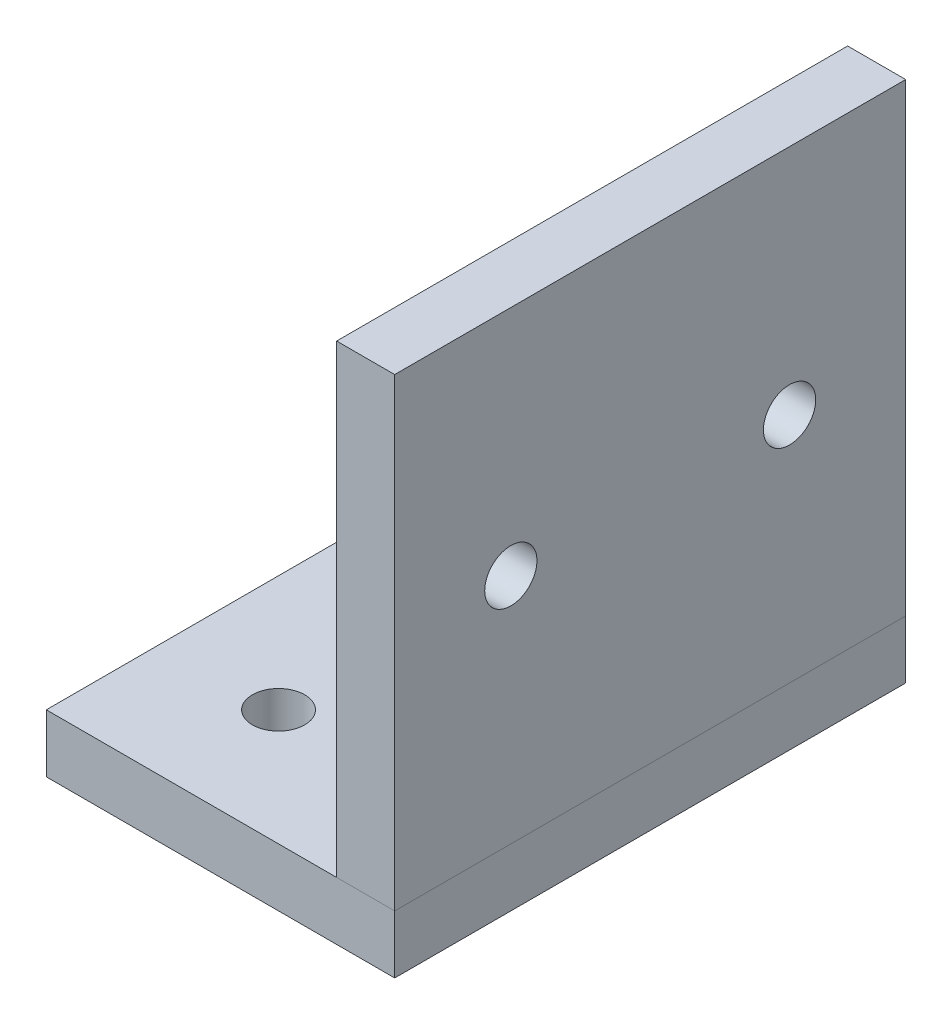
SolidWorks part; units mm, degrees
ref_plane "Front Plane" through (0, 0, 0) normal (0, 0, 1) x (1, 0, 0)
ref_plane "Top Plane" through (0, 0, 0) normal (0, 1, 0) x (1, 0, 0)
ref_plane "Right Plane" through (0, 0, 0) normal (1, 0, 0) x (0, 0, -1)
sketch "Sketch1" plane through (0, 0, 0) normal (0, 1, 0) x (1, 0, 0)
  line L1 (-15, -22) -> (15, -22)
  line L2 (-15, -22) -> (-15, 22)
  line L3 (-15, 22) -> (15, 22)
  line L4 (15, -22) -> (15, 22)
  line L5 (-15, -22) -> (15, 22) construction
  line L6 (-15, 22) -> (15, -22) construction
  point P0 (0, 0)
  dimension "D1" = 30
  dimension "D2" = 44
extrude "Boss-Extrude1" add sketch "Sketch1" along normal blind 5
sketch "Sketch2" plane through (0, 5, 0) normal (0, 1, 0) x (1, 0, 0)
  line L0 (-15, 22) -> (-15, -22) construction
  line L1 (-15, 0) -> (15, 0) construction
  line L2 (15, -22) -> (15, 22) construction
  circle A0 centre (-5, -12) radius 2.25
  circle A1 centre (-5, 12) radius 2.25
  point P4 (-12, 14.2176)
  point P5 (-12, 13.1493)
  point P8 (0, 0)
  point P9 (-5, 12.5)
  dimension "D1" = 4.5
  dimension "D2" = 24
  dimension "D3" = 10
  dimension "D4" = 12
extrude "Cut-Extrude1" cut sketch "Sketch2" against normal through all
sketch "Sketch4" plane through (0, 5, 0) normal (0, 1, 0) x (1, 0, 0)
  line L0 (-15, -22) -> (15, -22) construction
  line L2 (15, 22) -> (10, 22)
  line L3 (15, 22) -> (15, -22)
  line L4 (15, -22) -> (10, -22)
  line L5 (10, 22) -> (10, -22)
  dimension "D1" = 5
extrude "Boss-Extrude3" add sketch "Sketch4" along normal blind 40 separate body
sketch "Sketch5" plane through (10, 0, 0) normal (-1, 0, 0) x (0, 0, 1)
  line L0 (-22, 45) -> (22, 45) construction
  line L1 (-22, 45) -> (22, 45) construction
  line L2 (-22, 45) -> (-22, 5) construction
  circle A0 centre (12, 25) radius 2.25
  circle A1 centre (-12, 25) radius 2.25
  point P4 (11.0741, 95)
  point P5 (13.2769, 95)
  point P6 (13.0169, 95)
  point P9 (0, 0)
  point P12 (-10.9445, 55)
  point P13 (0, 0)
  dimension "D1" = 4.5
  dimension "D2" = 24
  dimension "D3" = 20
  dimension "D4" = 20
  dimension "D5" = 10
extrude "Cut-Extrude3" cut sketch "Sketch5" against normal through all
